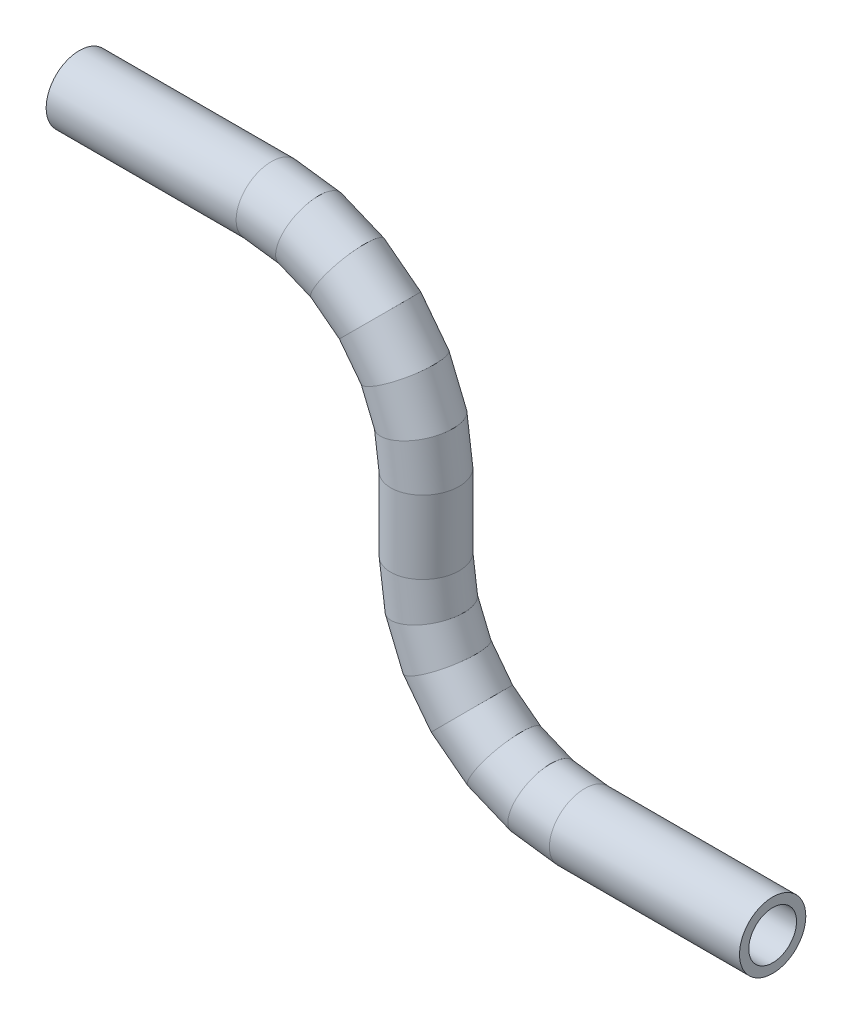
SolidWorks part; units mm, degrees
ref_plane "Front Plane" through (0, 0, 0) normal (0, 0, 1) x (1, 0, 0)
ref_plane "Top Plane" through (0, 0, 0) normal (0, 1, 0) x (1, 0, 0)
ref_plane "Right Plane" through (0, 0, 0) normal (1, 0, 0) x (0, 0, -1)
sketch3d "Path"
  line L0 (-2754.8928, 33, 0) -> (-2773.0928, 33, 0)
  line L1 (-2773.0928, 33, 0) -> (-2776.9751, 33.5111, 0)
  line L2 (-2776.9751, 33.5111, 0) -> (-2780.5928, 35.0096, 0)
  line L3 (-2780.5928, 35.0096, 0) -> (-2783.6994, 37.3934, 0)
  line L4 (-2783.6994, 37.3934, 0) -> (-2786.0832, 40.5, 0)
  line L5 (-2786.0832, 40.5, 0) -> (-2787.5817, 44.1177, 0)
  line L6 (-2787.5817, 44.1177, 0) -> (-2788.0928, 48, 0)
  line L7 (-2788.0928, 48, 0) -> (-2788.0928, 55, 0)
  line L8 (-2788.0928, 55, 0) -> (-2788.6039, 58.8823, 0)
  line L9 (-2788.6039, 58.8823, 0) -> (-2790.1024, 62.5, 0)
  line L10 (-2790.1024, 62.5, 0) -> (-2792.4862, 65.6066, 0)
  line L11 (-2792.4862, 65.6066, 0) -> (-2795.5928, 67.9904, 0)
  line L12 (-2795.5928, 67.9904, 0) -> (-2799.2105, 69.4889, 0)
  line L13 (-2799.2105, 69.4889, 0) -> (-2803.0928, 70, 0)
  line L14 (-2803.0928, 70, 0) -> (-2821.2928, 70, 0)
ref_plane "Start Plane" through (-2754.8928, 0, 0) normal (1, 0, 0) x (0, 0, -1)
sketch "Profile" plane through (-2754.8928, 0, 0) normal (1, 0, 0) x (0, 0, -1)
  circle A0 centre (0, 33) radius 3.175
  circle A1 centre (0, 33) radius 2.286
sweep "Tube" add profiles "Profile" path "Path"
